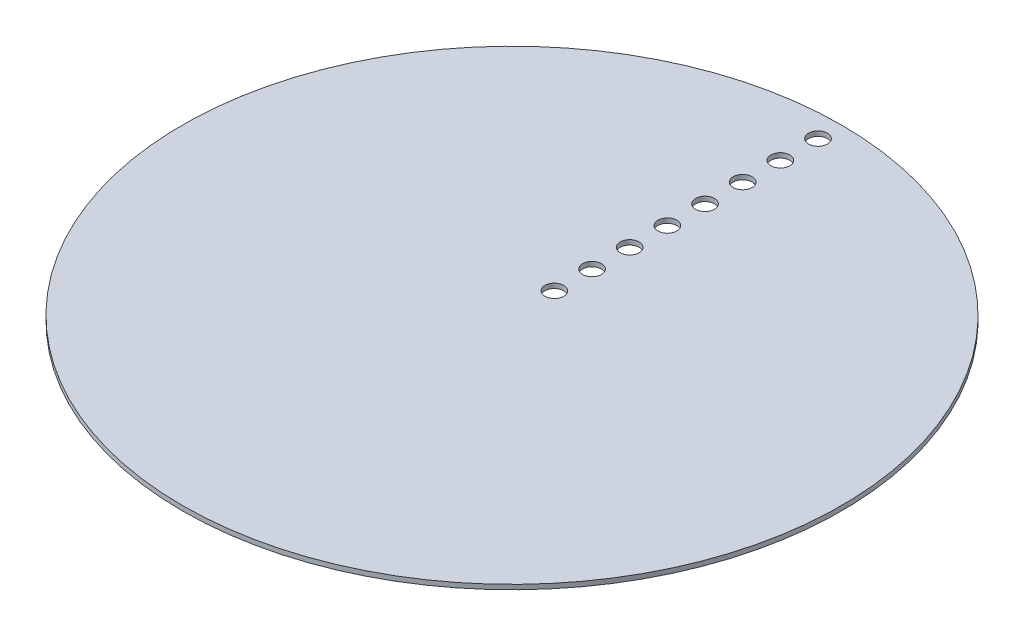
SolidWorks part; units mm, degrees
ref_plane "Front Plane" through (0, 0, 0) normal (0, 0, 1) x (1, 0, 0)
ref_plane "Top Plane" through (0, 0, 0) normal (0, 1, 0) x (1, 0, 0)
ref_plane "Right Plane" through (0, 0, 0) normal (1, 0, 0) x (0, 0, -1)
sketch "Sketch1" plane through (0, 0, 0) normal (0, 1, 0) x (1, 0, 0)
  circle A0 centre (0, 0) radius 70
  dimension "D1" = 140
extrude "Boss-Extrude1" add sketch "Sketch1" along normal blind 1
sketch "Sketch2" plane through (0, 1, 0) normal (0, 1, 0) x (1, 0, 0)
  line L0 (0, 0) -> (0, 70)
  line L1 (0, 0) -> (0, 25) construction
  line L2 (0, 0) -> (0, 33) construction
  line L3 (0, 0) -> (0, 41) construction
  circle A0 centre (0, 9) radius 2
  circle A1 centre (0, 0) radius 70 construction
  circle A2 centre (0, 17) radius 2
  circle A3 centre (0, 25) radius 2
  circle A4 centre (0, 33) radius 2
  circle A5 centre (0, 41) radius 2
  circle A6 centre (0, 49) radius 2
  circle A7 centre (0, 57) radius 2
  circle A8 centre (0, 65) radius 2
  circle A9 centre (7.7942, 4.5) radius 2
  circle A10 centre (7.7942, -4.5) radius 2
  circle A11 centre (0, -9) radius 2
  circle A12 centre (-7.7942, -4.5) radius 2
  circle A13 centre (-7.7942, 4.5) radius 2
  circle A14 centre (8.5, 14.7224) radius 2
  circle A15 centre (14.7224, 8.5) radius 2
  circle A16 centre (17, 0) radius 2
  circle A17 centre (14.7224, -8.5) radius 2
  circle A18 centre (8.5, -14.7224) radius 2
  circle A19 centre (0, -17) radius 2
  circle A20 centre (-8.5, -14.7224) radius 2
  circle A21 centre (-14.7224, -8.5) radius 2
  circle A22 centre (-17, 0) radius 2
  circle A23 centre (-14.7224, 8.5) radius 2
  circle A24 centre (-8.5, 14.7224) radius 2
  circle A25 centre (8.5505, 23.4923) radius 2
  circle A26 centre (16.0697, 19.1511) radius 2
  circle A27 centre (21.6506, 12.5) radius 2
  circle A28 centre (24.6202, 4.3412) radius 2
  circle A29 centre (24.6202, -4.3412) radius 2
  circle A30 centre (21.6506, -12.5) radius 2
  circle A31 centre (16.0697, -19.1511) radius 2
  circle A32 centre (8.5505, -23.4923) radius 2
  circle A33 centre (0, -25) radius 2
  circle A34 centre (-8.5505, -23.4923) radius 2
  circle A35 centre (-16.0697, -19.1511) radius 2
  circle A36 centre (-21.6506, -12.5) radius 2
  circle A37 centre (-24.6202, -4.3412) radius 2
  circle A38 centre (-24.6202, 4.3412) radius 2
  circle A39 centre (-21.6506, 12.5) radius 2
  circle A40 centre (-16.0697, 19.1511) radius 2
  circle A41 centre (-8.5505, 23.4923) radius 2
  circle A42 centre (8.541, 31.8756) radius 2
  circle A43 centre (16.5, 28.5788) radius 2
  circle A44 centre (23.3345, 23.3345) radius 2
  circle A45 centre (28.5788, 16.5) radius 2
  circle A46 centre (31.8756, 8.541) radius 2
  circle A47 centre (33, 0) radius 2
  circle A48 centre (31.8756, -8.541) radius 2
  circle A49 centre (28.5788, -16.5) radius 2
  circle A50 centre (23.3345, -23.3345) radius 2
  circle A51 centre (16.5, -28.5788) radius 2
  circle A52 centre (8.541, -31.8756) radius 2
  circle A53 centre (0, -33) radius 2
  circle A54 centre (-8.541, -31.8756) radius 2
  circle A55 centre (-16.5, -28.5788) radius 2
  circle A56 centre (-23.3345, -23.3345) radius 2
  circle A57 centre (-28.5788, -16.5) radius 2
  circle A58 centre (-31.8756, -8.541) radius 2
  circle A59 centre (-33, 0) radius 2
  circle A60 centre (-31.8756, 8.541) radius 2
  circle A61 centre (-28.5788, 16.5) radius 2
  circle A62 centre (-23.3345, 23.3345) radius 2
  circle A63 centre (-16.5, 28.5788) radius 2
  circle A64 centre (-8.541, 31.8756) radius 2
  circle A65 centre (8.5244, 40.1041) radius 2
  circle A66 centre (16.6762, 37.4554) radius 2
  circle A67 centre (24.0992, 33.1697) radius 2
  circle A68 centre (30.4689, 27.4344) radius 2
  circle A69 centre (35.507, 20.5) radius 2
  circle A70 centre (38.9933, 12.6697) radius 2
  circle A71 centre (40.7754, 4.2857) radius 2
  circle A72 centre (40.7754, -4.2857) radius 2
  circle A73 centre (38.9933, -12.6697) radius 2
  circle A74 centre (35.507, -20.5) radius 2
  circle A75 centre (30.4689, -27.4344) radius 2
  circle A76 centre (24.0992, -33.1697) radius 2
  circle A77 centre (16.6762, -37.4554) radius 2
  circle A78 centre (8.5244, -40.1041) radius 2
  circle A79 centre (0, -41) radius 2
  circle A80 centre (-8.5244, -40.1041) radius 2
  circle A81 centre (-16.6762, -37.4554) radius 2
  circle A82 centre (-24.0992, -33.1697) radius 2
  circle A83 centre (-30.4689, -27.4344) radius 2
  circle A84 centre (-35.507, -20.5) radius 2
  circle A85 centre (-38.9933, -12.6697) radius 2
  circle A86 centre (-40.7754, -4.2857) radius 2
  circle A87 centre (-40.7754, 4.2857) radius 2
  circle A88 centre (-38.9933, 12.6697) radius 2
  circle A89 centre (-35.507, 20.5) radius 2
  circle A90 centre (-30.4689, 27.4344) radius 2
  circle A91 centre (-24.0992, 33.1697) radius 2
  circle A92 centre (-16.6762, 37.4554) radius 2
  circle A93 centre (-8.5244, 40.1041) radius 2
  point P33 (0, 0)
  point P57 (0, 0)
  dimension "D1" = 4
  dimension "D2" = 9
  dimension "D7" = 25
  dimension "D9" = 33
  dimension "D11" = 41
  dimension "D3" = 8
  dimension "D4" = 6
  dimension "D5" = 12
  dimension "D6" = 18
  dimension "D8" = 24
  dimension "D10" = 30
extrude "Cut-Extrude1" cut sketch "Sketch2" against normal blind 1 contours A0 | A2 | A3 | A4 | A5 | A6 | A7 | A8
